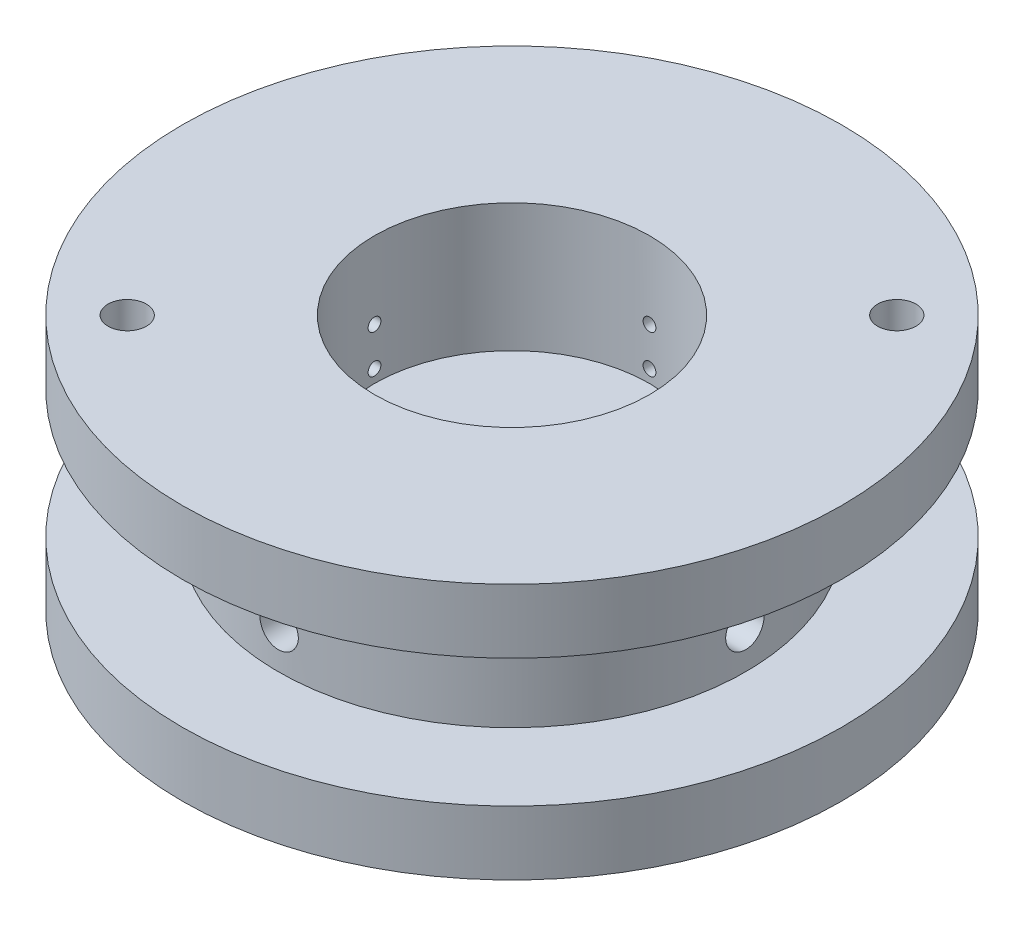
SolidWorks part; units mm, degrees
ref_plane "Front Plane" through (0, 0, 0) normal (0, 0, 1) x (1, 0, 0)
ref_plane "Top Plane" through (0, 0, 0) normal (0, 1, 0) x (1, 0, 0)
ref_plane "Right Plane" through (0, 0, 0) normal (1, 0, 0) x (0, 0, -1)
sketch "Sketch2" plane through (0, 0, 0) normal (0, 0, 1) x (1, 0, 0)
  line L0 (0, 87.5455) -> (0, -67.9094) construction
  line L1 (3.25, 0) -> (10.75, 0)
  line L2 (10.75, 0) -> (10.75, 2)
  line L3 (10.75, 2) -> (25.75, 2)
  line L4 (25.75, 2) -> (25.75, 7)
  line L5 (25.75, 7) -> (18.25, 7)
  line L6 (18.25, 7) -> (18.25, 17)
  line L7 (18.25, 17) -> (25.75, 17)
  line L8 (25.75, 17) -> (25.75, 22)
  line L9 (25.75, 22) -> (10.75, 22)
  line L10 (10.75, 22) -> (10.75, 12)
  line L11 (10.75, 12) -> (3.25, 12)
  line L12 (3.25, 12) -> (3.25, 0)
  dimension "D1" = 3.25
  dimension "D2" = 7.5
  dimension "D3" = 7.5
  dimension "D4" = 7.5
  dimension "D5" = 7.5
  dimension "D6" = 5
  dimension "D7" = 2
  dimension "D8" = 10
  dimension "D9" = 5
  dimension "D10" = 12
revolve "Revolve1" add sketch "Sketch2" angle 360 about L0
sketch "Sketch3" plane through (0, 0, 0) normal (1, 0, 0) x (0, 0, -1)
  line L0 (0, 22) -> (0, 2) construction
  line L1 (10.75, 22) -> (-10.75, 22) construction
  line L2 (-10.75, 2) -> (10.75, 2) construction
  line L3 (25.75, 7) -> (-25.75, 7) construction
  circle A0 centre (0, 13) radius 0.5
  circle A1 centre (0, 16) radius 0.5
  circle A2 centre (0, 10) radius 1.5
  dimension "D1" = 1
  dimension "D2" = 1
  dimension "D5" = 3
  dimension "D3" = 6
  dimension "D4" = 3
  dimension "D6" = 3
extrude "Cut-Extrude1" cut sketch "Sketch3" against normal through all both and the other way through all
pattern_circular "CirPattern1" count 2 every 90 about axis through (0, 22, 0) along (0, 1, 0) of "Cut-Extrude1"
sketch "Sketch4" plane through (0, 22, 0) normal (0, 1, 0) x (1, 0, 0)
  line L0 (0, 14.1042) -> (0, -14.404) construction
  line L1 (-15.026, -15.026) -> (15.026, 15.026) construction
  circle A0 centre (15.026, 15.026) radius 1.5
  circle A1 centre (-15.026, -15.026) radius 1.5
  point P12 (0, 0)
  dimension "D3" = 3
  dimension "D4" = 3
  dimension "D5" = 45
  dimension "D6" = 42.5
extrude "Cut-Extrude2" cut sketch "Sketch4" against normal blind 13
